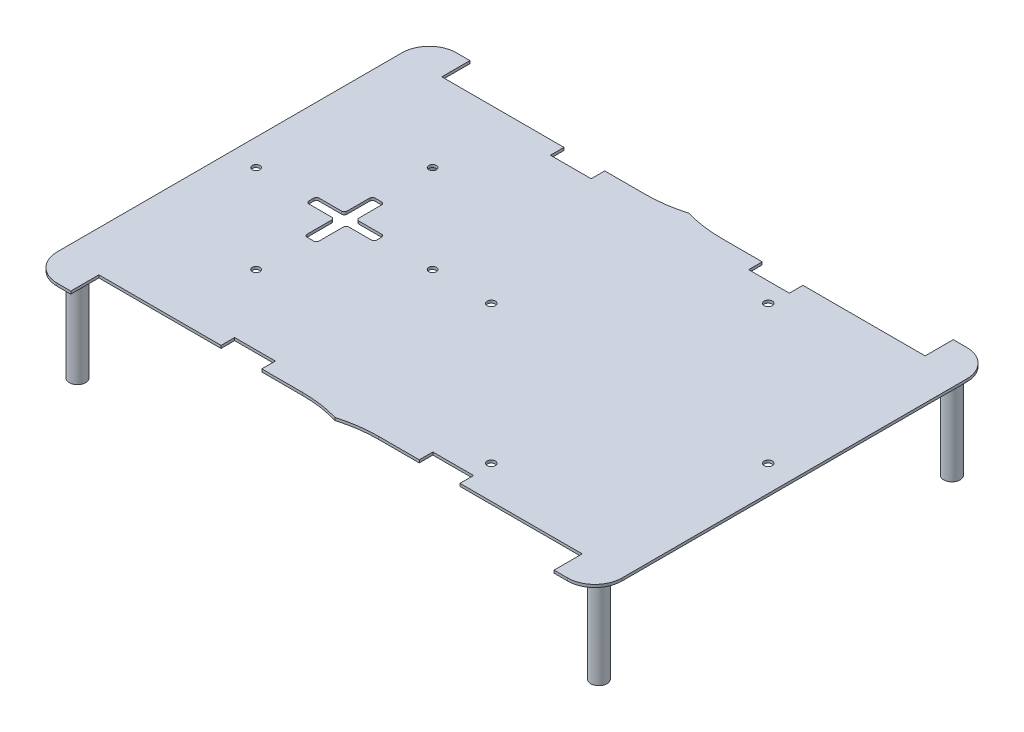
SolidWorks part; units mm, degrees
ref_plane "Front Plane" through (0, 0, 0) normal (0, 0, 1) x (1, 0, 0)
ref_plane "Top Plane" through (0, 0, 0) normal (0, 1, 0) x (1, 0, 0)
ref_plane "Right Plane" through (0, 0, 0) normal (1, 0, 0) x (0, 0, -1)
sketch "Sketch1" plane through (0, 0, 0) normal (0, 1, 0) x (1, 0, 0)
  line L1 (-104, -73.5) -> (104, -73.5)
  line L2 (-104, -73.5) -> (-104, 73.5)
  line L3 (-104, 73.5) -> (104, 73.5)
  line L4 (104, -73.5) -> (104, 73.5)
  line L5 (-104, -73.5) -> (104, 73.5) construction
  line L6 (-104, 73.5) -> (104, -73.5) construction
  point P0 (0, 0)
  dimension "D1" = 208
  dimension "D2" = 147
extrude "Boss-Extrude1" add sketch "Sketch1" along normal blind 1
sketch "Sketch3" plane through (0, 1, 0) normal (0, 1, 0) x (1, 0, 0)
  line L0 (-89, 83.1455) -> (-89, 63.1455)
  line L1 (-89, 63.1455) -> (-44, 63.1455)
  line L2 (-44, 58.1455) -> (-29, 58.1455)
  line L3 (-29, 58.1455) -> (-29, 63.1455)
  line L4 (-29, 63.1455) -> (-14, 63.1455)
  line L5 (0, 65.1455) -> (0, 85.1455)
  line L6 (0, 85.1455) -> (-89, 85.1455)
  line L7 (-89, 85.1455) -> (-89, 83.1455)
  line L8 (-44, 63.1455) -> (-44, 58.1455)
  line L9 (-104, 73.5) -> (-104, -73.5) construction
  arc A0 (-14, 63.1455) -> (0, 65.1455) centre (-14, 113.1455) ccw
  dimension "D8" = 20
  dimension "D7" = 50
  dimension "D1" = 20
  dimension "D2" = 45
  dimension "D3" = 15
  dimension "D4" = 15
  dimension "D5" = 5
  dimension "D6" = 5
  dimension "D9" = 15
extrude "Cut-Extrude1" cut sketch "Sketch3" against normal through all
mirror "Mirror1" about plane through (0, 0, 0) normal (0, 0, 1) of "Cut-Extrude1"
mirror "Mirror2" about plane through (0, 0, 0) normal (1, 0, 0) of "Mirror1", "Cut-Extrude1"
fillet "Fillet1" radius 10 4 edges at (-104, 0.5, 73.5) (104, 0.5, -73.5) (-104, 0.5, -73.5) (104, 0.5, 73.5)
sketch "Sketch4" plane through (0, 0, 0) normal (0, -1, 0) x (1, 0, 0)
  line L0 (-58.2258, 1.8762) -> (-49.9249, 1.8762)
  line L5 (-62.6239, -12.1762) -> (-60.2258, -12.1762)
  line L6 (-63.6239, -11.1762) -> (-63.6239, -2.8762)
  line L11 (-62.6239, 12.8238) -> (-60.2258, 12.8238)
  line L12 (-59.2258, -11.1762) -> (-59.2258, -2.8762)
  line L13 (-59.2258, 2.8762) -> (-59.2258, 11.8238)
  line L14 (-63.6239, 2.8762) -> (-63.6239, 11.8238)
  line L15 (-72.9249, -1.8762) -> (-64.6239, -1.8762)
  line L16 (-73.9249, -0.8762) -> (-73.9249, 0.8762)
  line L17 (-72.9249, 1.8762) -> (-64.6239, 1.8762)
  line L18 (-48.9249, -0.8762) -> (-48.9249, 0.8762)
  line L19 (-73.9249, 0) -> (-48.9249, 0) construction
  line L20 (-61.4249, -12.1762) -> (-61.4249, 12.8238) construction
  line L21 (0, 0) -> (-61.4249, 0) construction
  line L26 (-58.2258, -1.8762) -> (-49.9249, -1.8762)
  arc A0 (-73.9249, 0.8762) -> (-72.9249, 1.8762) centre (-72.9249, 0.8762) cw
  arc A1 (-72.9249, -1.8762) -> (-73.9249, -0.8762) centre (-72.9249, -0.8762) cw
  arc A2 (-64.6239, -1.8762) -> (-63.6239, -2.8762) centre (-64.6239, -2.8762) cw
  arc A3 (-62.6239, -12.1762) -> (-63.6239, -11.1762) centre (-62.6239, -11.1762) cw
  arc A4 (-60.2258, -12.1762) -> (-59.2258, -11.1762) centre (-60.2258, -11.1762) ccw
  arc A5 (-58.2258, -1.8762) -> (-59.2258, -2.8762) centre (-58.2258, -2.8762) ccw
  arc A6 (-49.9249, -1.8762) -> (-48.9249, -0.8762) centre (-49.9249, -0.8762) ccw
  arc A7 (-49.9249, 1.8762) -> (-48.9249, 0.8762) centre (-49.9249, 0.8762) cw
  arc A8 (-60.2258, 12.8238) -> (-59.2258, 11.8238) centre (-60.2258, 11.8238) cw
  arc A9 (-63.6239, 11.8238) -> (-62.6239, 12.8238) centre (-62.6239, 11.8238) cw
  arc A10 (-64.6239, 1.8762) -> (-63.6239, 2.8762) centre (-64.6239, 2.8762) ccw
  arc A11 (-58.2258, 1.8762) -> (-59.2258, 2.8762) centre (-58.2258, 2.8762) cw
  point P0 (-61.4249, 0)
  point P5 (-61.4249, 0)
  point P24 (-59.2258, -12.1762)
  point P33 (-59.2258, 12.8238)
  point P38 (-63.6239, 1.8762)
  point P43 (-61.4249, 12.8238)
  point P44 (-61.4249, -12.1762)
  point P47 (-59.2258, 1.8762)
  point P51 (-61.4249, 0)
  dimension "D2" = 1
  dimension "D6" = 8.3009
  dimension "D4" = 1
  dimension "D8" = 8.3
  dimension "D1" = 25
  dimension "D3" = 25
  dimension "D5" = 8.3009
  dimension "D7" = 8.3
  dimension "D9" = 1.7525
extrude "Cut-Extrude2" cut sketch "Sketch4" against normal through all
sketch "Sketch7" plane through (0, 0, 0) normal (0, -1, 0) x (1, 0, 0)
  line L0 (0, 0) -> (-126.8797, 0) construction
  line L1 (0, 0) -> (112.306, 0) construction
  circle A2 centre (43.369, 51) radius 1.5
  circle A3 centre (-7.631, 0) radius 1.5
  circle A4 centre (94.369, 0) radius 1.5
  circle A5 centre (43.369, -51) radius 1.5
  dimension "D3" = 3
  dimension "D4" = 3
  dimension "D5" = 3
  dimension "D6" = 3
extrude "Cut-Extrude3" cut sketch "Sketch7" against normal through all
sketch "Sketch8" plane through (0, 1, 0) normal (0, 1, 0) x (1, 0, 0)
  line L0 (0, 0) -> (-104, 0) construction
  line L1 (-104, 63.5) -> (-104, -63.5) construction
  line L2 (0, 0) -> (104, 0) construction
  line L3 (104, -63.5) -> (104, 63.5) construction
  line L4 (-104, 65) -> (104, 65) construction
  line L5 (-104, 63.5) -> (-104, -63.5) construction
  line L6 (104, -63.5) -> (104, 63.5) construction
  line L7 (-104, -65) -> (104, -65) construction
  line L8 (-95, 65) -> (-95, -65) construction
  line L9 (97, 65) -> (97, -65) construction
  circle A0 centre (-95, 65) radius 3
  circle A1 centre (-95, -65) radius 3
  circle A2 centre (97, -65) radius 3
  circle A3 centre (97, 65) radius 3
  dimension "D4" = 6
  dimension "D5" = 6
  dimension "D6" = 6
  dimension "D7" = 6
  dimension "D1" = 65
  dimension "D2" = 9
  dimension "D3" = 7
extrude "Boss-Extrude3" add sketch "Sketch8" against normal blind 35
sketch "Sketch9" plane through (0, 1, 0) normal (0, 1, 0) x (1, 0, 0)
  circle A0 centre (-61.7401, 0) radius 32.5 construction
  circle A1 centre (-61.7401, 32.5) radius 1.4
  circle A2 centre (-94.2401, 0) radius 1.4
  circle A3 centre (-61.7401, -32.5) radius 1.4
  circle A4 centre (-29.2401, 0) radius 1.4
  dimension "D1" = 65
  dimension "D2" = 2.8
extrude "Cut-Extrude4" cut sketch "Sketch9" against normal blind 60
